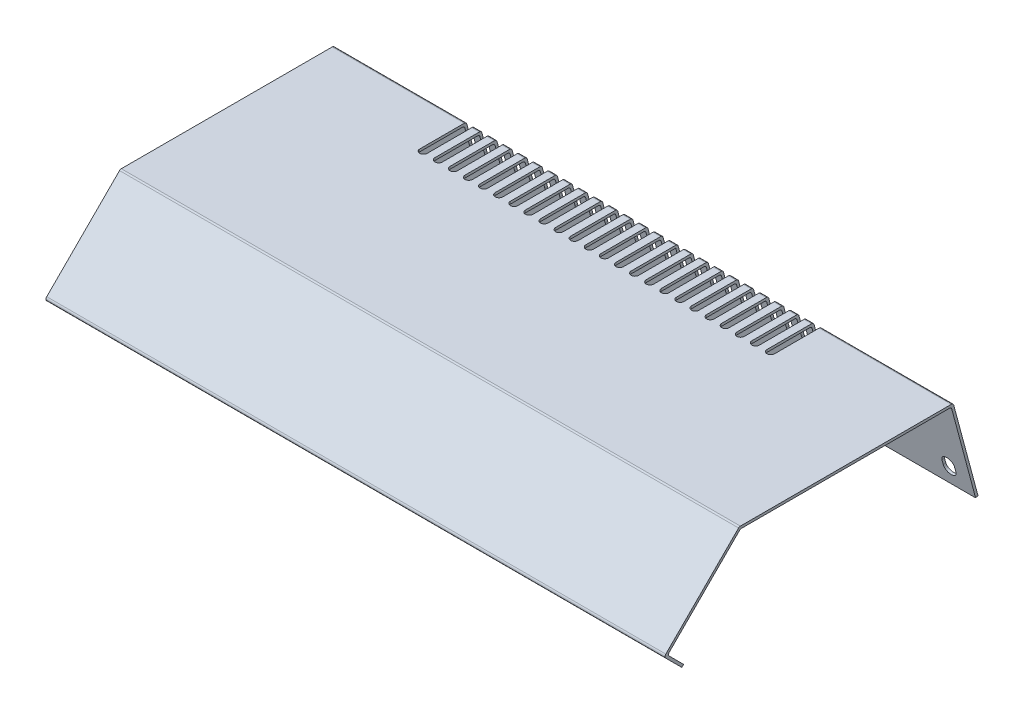
SolidWorks part; units mm, degrees
material "1023 Листовая углеродистая сталь (SS)"
ref_plane "Спереди" through (0, 0, 0) normal (0, 0, 1) x (1, 0, 0)
ref_plane "Сверху" through (0, 0, 0) normal (0, 1, 0) x (1, 0, 0)
ref_plane "Справа" through (0, 0, 0) normal (1, 0, 0) x (0, 0, -1)
sketch "Эскиз1" plane through (0, 0, 0) normal (1, 0, 0) x (0, 0, -1)
  line L2 (-42.5, 37) -> (42.5, 37)
  line L3 (-72.4289, 7.0711) -> (-42.5, 37)
  line L4 (42.5, 37) -> (52.3448, 0.2588)
  line L14 (-72.4289, 7.0711) -> (-65.3579, 0)
  line L15 (-71.0147, 7.0711) -> (-64.6508, 0.7071)
  line L16 (-71.0147, 7.0711) -> (-42.0858, 36)
  line L17 (-42.0858, 36) -> (41.7327, 36)
  line L18 (41.7327, 36) -> (51.3788, 0)
  line L19 (-65.3579, 0) -> (-64.6508, 0.7071)
  line L20 (51.3788, 0) -> (52.3448, 0.2588)
  point P8 (0, 37)
  dimension "D1" = 105
  dimension "D2" = 37
  dimension "D3" = 85
  dimension "D4" = 135
  dimension "D5" = 10
  dimension "D6" = 1
extrude "Бобышка-Вытянуть1" add sketch "Эскиз1" along normal mid plane 246
sketch "Эскиз2" plane through (0, 37, 0) normal (0, 1, 0) x (1, 0, 0)
  line L0 (0, 0) -> (0, 58.0016) construction
  line L1 (-70.5, 42.5) -> (-70.5, 24)
  line L2 (-70.5, 42.5) -> (-67.5, 42.5)
  line L3 (-67.5, 42.5) -> (-67.5, 24)
  line L4 (123, 42.5) -> (-123, 42.5) construction
  line L5 (-64.5, 42.5) -> (-64.5, 24)
  line L6 (-61.5, 42.5) -> (-61.5, 24)
  line L7 (-64.5, 42.5) -> (-61.5, 42.5)
  line L8 (-58.5, 42.5) -> (-58.5, 24)
  line L9 (-55.5, 42.5) -> (-55.5, 24)
  line L10 (-58.5, 42.5) -> (-55.5, 42.5)
  line L11 (-52.5, 42.5) -> (-52.5, 24)
  line L12 (-49.5, 42.5) -> (-49.5, 24)
  line L13 (-52.5, 42.5) -> (-49.5, 42.5)
  line L14 (-46.5, 42.5) -> (-46.5, 24)
  line L15 (-43.5, 42.5) -> (-43.5, 24)
  line L16 (-46.5, 42.5) -> (-43.5, 42.5)
  line L17 (-40.5, 42.5) -> (-40.5, 24)
  line L18 (-37.5, 42.5) -> (-37.5, 24)
  line L19 (-40.5, 42.5) -> (-37.5, 42.5)
  line L20 (-34.5, 42.5) -> (-34.5, 24)
  line L21 (-31.5, 42.5) -> (-31.5, 24)
  line L22 (-34.5, 42.5) -> (-31.5, 42.5)
  line L23 (-28.5, 42.5) -> (-28.5, 24)
  line L24 (-25.5, 42.5) -> (-25.5, 24)
  line L25 (-28.5, 42.5) -> (-25.5, 42.5)
  line L26 (-22.5, 42.5) -> (-22.5, 24)
  line L27 (-19.5, 42.5) -> (-19.5, 24)
  line L28 (-22.5, 42.5) -> (-19.5, 42.5)
  line L29 (-16.5, 42.5) -> (-16.5, 24)
  line L30 (-13.5, 42.5) -> (-13.5, 24)
  line L31 (-16.5, 42.5) -> (-13.5, 42.5)
  line L32 (-10.5, 42.5) -> (-10.5, 24)
  line L33 (-7.5, 42.5) -> (-7.5, 24)
  line L34 (-10.5, 42.5) -> (-7.5, 42.5)
  line L35 (-4.5, 42.5) -> (-4.5, 24)
  line L36 (-1.5, 42.5) -> (-1.5, 24)
  line L37 (-4.5, 42.5) -> (-1.5, 42.5)
  line L38 (1.5, 42.5) -> (1.5, 24)
  line L39 (4.5, 42.5) -> (4.5, 24)
  line L40 (1.5, 42.5) -> (4.5, 42.5)
  line L41 (7.5, 42.5) -> (7.5, 24)
  line L42 (10.5, 42.5) -> (10.5, 24)
  line L43 (7.5, 42.5) -> (10.5, 42.5)
  line L44 (13.5, 42.5) -> (13.5, 24)
  line L45 (16.5, 42.5) -> (16.5, 24)
  line L46 (13.5, 42.5) -> (16.5, 42.5)
  line L47 (19.5, 42.5) -> (19.5, 24)
  line L48 (22.5, 42.5) -> (22.5, 24)
  line L49 (19.5, 42.5) -> (22.5, 42.5)
  line L50 (25.5, 42.5) -> (25.5, 24)
  line L51 (28.5, 42.5) -> (28.5, 24)
  line L52 (25.5, 42.5) -> (28.5, 42.5)
  line L53 (31.5, 42.5) -> (31.5, 24)
  line L54 (34.5, 42.5) -> (34.5, 24)
  line L55 (31.5, 42.5) -> (34.5, 42.5)
  line L56 (37.5, 42.5) -> (37.5, 24)
  line L57 (40.5, 42.5) -> (40.5, 24)
  line L58 (37.5, 42.5) -> (40.5, 42.5)
  line L59 (43.5, 42.5) -> (43.5, 24)
  line L60 (46.5, 42.5) -> (46.5, 24)
  line L61 (43.5, 42.5) -> (46.5, 42.5)
  line L62 (49.5, 42.5) -> (49.5, 24)
  line L63 (52.5, 42.5) -> (52.5, 24)
  line L64 (49.5, 42.5) -> (52.5, 42.5)
  line L65 (55.5, 42.5) -> (55.5, 24)
  line L66 (58.5, 42.5) -> (58.5, 24)
  line L67 (55.5, 42.5) -> (58.5, 42.5)
  line L68 (61.5, 42.5) -> (61.5, 24)
  line L69 (64.5, 42.5) -> (64.5, 24)
  line L70 (61.5, 42.5) -> (64.5, 42.5)
  line L71 (67.5, 42.5) -> (67.5, 24)
  line L72 (70.5, 42.5) -> (70.5, 24)
  line L73 (67.5, 42.5) -> (70.5, 42.5)
  arc A0 (-67.5, 24) -> (-70.5, 24) centre (-69, 24) cw
  arc A1 (-61.5, 24) -> (-64.5, 24) centre (-63, 24) cw
  arc A2 (-55.5, 24) -> (-58.5, 24) centre (-57, 24) cw
  arc A3 (-49.5, 24) -> (-52.5, 24) centre (-51, 24) cw
  arc A4 (-43.5, 24) -> (-46.5, 24) centre (-45, 24) cw
  arc A5 (-37.5, 24) -> (-40.5, 24) centre (-39, 24) cw
  arc A6 (-31.5, 24) -> (-34.5, 24) centre (-33, 24) cw
  arc A7 (-25.5, 24) -> (-28.5, 24) centre (-27, 24) cw
  arc A8 (-19.5, 24) -> (-22.5, 24) centre (-21, 24) cw
  arc A9 (-13.5, 24) -> (-16.5, 24) centre (-15, 24) cw
  arc A10 (-7.5, 24) -> (-10.5, 24) centre (-9, 24) cw
  arc A11 (-1.5, 24) -> (-4.5, 24) centre (-3, 24) cw
  arc A12 (4.5, 24) -> (1.5, 24) centre (3, 24) cw
  arc A13 (10.5, 24) -> (7.5, 24) centre (9, 24) cw
  arc A14 (16.5, 24) -> (13.5, 24) centre (15, 24) cw
  arc A15 (22.5, 24) -> (19.5, 24) centre (21, 24) cw
  arc A16 (28.5, 24) -> (25.5, 24) centre (27, 24) cw
  arc A17 (34.5, 24) -> (31.5, 24) centre (33, 24) cw
  arc A18 (40.5, 24) -> (37.5, 24) centre (39, 24) cw
  arc A19 (46.5, 24) -> (43.5, 24) centre (45, 24) cw
  arc A20 (52.5, 24) -> (49.5, 24) centre (51, 24) cw
  arc A21 (58.5, 24) -> (55.5, 24) centre (57, 24) cw
  arc A22 (64.5, 24) -> (61.5, 24) centre (63, 24) cw
  arc A23 (70.5, 24) -> (67.5, 24) centre (69, 24) cw
  point P10 (-69, 22.5)
  dimension "D1" = 3
  dimension "D2" = 20
  dimension "D3" = 24
extrude "Вырез-Вытянуть1" cut sketch "Эскиз2" against normal blind 10
sketch "Эскиз3" plane through (0, 13.1035, -48.903) normal (0, 0.2588, -0.9659) x (-1, 0, 0)
  line L0 (0, 0) -> (0, 49.0276) construction
  line L1 (-70.5, 24.7394) -> (-70.5, 16.2394)
  line L2 (-67.5, 24.7394) -> (-67.5, 16.2394)
  line L3 (-70.5, 24.7394) -> (-67.5, 24.7394)
  line L4 (-64.5, 24.7394) -> (-61.5, 24.7394)
  line L5 (-64.5, 24.7394) -> (-64.5, 16.2394)
  line L6 (-61.5, 24.7394) -> (-61.5, 16.2394)
  line L7 (-58.5, 24.7394) -> (-55.5, 24.7394)
  line L8 (-58.5, 24.7394) -> (-58.5, 16.2394)
  line L9 (-55.5, 24.7394) -> (-55.5, 16.2394)
  line L10 (-52.5, 24.7394) -> (-49.5, 24.7394)
  line L11 (-52.5, 24.7394) -> (-52.5, 16.2394)
  line L12 (-49.5, 24.7394) -> (-49.5, 16.2394)
  line L13 (-46.5, 24.7394) -> (-43.5, 24.7394)
  line L14 (-46.5, 24.7394) -> (-46.5, 16.2394)
  line L15 (-43.5, 24.7394) -> (-43.5, 16.2394)
  line L16 (-40.5, 24.7394) -> (-37.5, 24.7394)
  line L17 (-40.5, 24.7394) -> (-40.5, 16.2394)
  line L18 (-37.5, 24.7394) -> (-37.5, 16.2394)
  line L19 (-34.5, 24.7394) -> (-31.5, 24.7394)
  line L20 (-34.5, 24.7394) -> (-34.5, 16.2394)
  line L21 (-31.5, 24.7394) -> (-31.5, 16.2394)
  line L22 (-28.5, 24.7394) -> (-25.5, 24.7394)
  line L23 (-28.5, 24.7394) -> (-28.5, 16.2394)
  line L24 (-25.5, 24.7394) -> (-25.5, 16.2394)
  line L25 (-22.5, 24.7394) -> (-19.5, 24.7394)
  line L26 (-22.5, 24.7394) -> (-22.5, 16.2394)
  line L27 (-19.5, 24.7394) -> (-19.5, 16.2394)
  line L28 (-16.5, 24.7394) -> (-13.5, 24.7394)
  line L29 (-16.5, 24.7394) -> (-16.5, 16.2394)
  line L30 (-13.5, 24.7394) -> (-13.5, 16.2394)
  line L31 (-10.5, 24.7394) -> (-7.5, 24.7394)
  line L32 (-10.5, 24.7394) -> (-10.5, 16.2394)
  line L33 (-7.5, 24.7394) -> (-7.5, 16.2394)
  line L34 (-4.5, 24.7394) -> (-1.5, 24.7394)
  line L35 (-4.5, 24.7394) -> (-4.5, 16.2394)
  line L36 (-1.5, 24.7394) -> (-1.5, 16.2394)
  line L37 (1.5, 24.7394) -> (4.5, 24.7394)
  line L38 (1.5, 24.7394) -> (1.5, 16.2394)
  line L39 (4.5, 24.7394) -> (4.5, 16.2394)
  line L40 (7.5, 24.7394) -> (10.5, 24.7394)
  line L41 (7.5, 24.7394) -> (7.5, 16.2394)
  line L42 (10.5, 24.7394) -> (10.5, 16.2394)
  line L43 (13.5, 24.7394) -> (16.5, 24.7394)
  line L44 (13.5, 24.7394) -> (13.5, 16.2394)
  line L45 (16.5, 24.7394) -> (16.5, 16.2394)
  line L46 (19.5, 24.7394) -> (22.5, 24.7394)
  line L47 (19.5, 24.7394) -> (19.5, 16.2394)
  line L48 (22.5, 24.7394) -> (22.5, 16.2394)
  line L49 (25.5, 24.7394) -> (28.5, 24.7394)
  line L50 (25.5, 24.7394) -> (25.5, 16.2394)
  line L51 (28.5, 24.7394) -> (28.5, 16.2394)
  line L52 (31.5, 24.7394) -> (34.5, 24.7394)
  line L53 (31.5, 24.7394) -> (31.5, 16.2394)
  line L54 (34.5, 24.7394) -> (34.5, 16.2394)
  line L55 (37.5, 24.7394) -> (40.5, 24.7394)
  line L56 (37.5, 24.7394) -> (37.5, 16.2394)
  line L57 (40.5, 24.7394) -> (40.5, 16.2394)
  line L58 (43.5, 24.7394) -> (46.5, 24.7394)
  line L59 (43.5, 24.7394) -> (43.5, 16.2394)
  line L60 (46.5, 24.7394) -> (46.5, 16.2394)
  line L61 (49.5, 24.7394) -> (52.5, 24.7394)
  line L62 (49.5, 24.7394) -> (49.5, 16.2394)
  line L63 (52.5, 24.7394) -> (52.5, 16.2394)
  line L64 (55.5, 24.7394) -> (58.5, 24.7394)
  line L65 (55.5, 24.7394) -> (55.5, 16.2394)
  line L66 (58.5, 24.7394) -> (58.5, 16.2394)
  line L67 (61.5, 24.7394) -> (64.5, 24.7394)
  line L68 (61.5, 24.7394) -> (61.5, 16.2394)
  line L69 (64.5, 24.7394) -> (64.5, 16.2394)
  line L70 (67.5, 24.7394) -> (70.5, 24.7394)
  line L71 (67.5, 24.7394) -> (67.5, 16.2394)
  line L72 (70.5, 24.7394) -> (70.5, 16.2394)
  line L73 (-70.5, 24.7394) -> (-64.5, 24.7394) construction
  arc A0 (-67.5, 16.2394) -> (-70.5, 16.2394) centre (-69, 16.2394) cw
  arc A1 (-61.5, 16.2394) -> (-64.5, 16.2394) centre (-63, 16.2394) cw
  arc A2 (-55.5, 16.2394) -> (-58.5, 16.2394) centre (-57, 16.2394) cw
  arc A3 (-49.5, 16.2394) -> (-52.5, 16.2394) centre (-51, 16.2394) cw
  arc A4 (-43.5, 16.2394) -> (-46.5, 16.2394) centre (-45, 16.2394) cw
  arc A5 (-37.5, 16.2394) -> (-40.5, 16.2394) centre (-39, 16.2394) cw
  arc A6 (-31.5, 16.2394) -> (-34.5, 16.2394) centre (-33, 16.2394) cw
  arc A7 (-25.5, 16.2394) -> (-28.5, 16.2394) centre (-27, 16.2394) cw
  arc A8 (-19.5, 16.2394) -> (-22.5, 16.2394) centre (-21, 16.2394) cw
  arc A9 (-13.5, 16.2394) -> (-16.5, 16.2394) centre (-15, 16.2394) cw
  arc A10 (-7.5, 16.2394) -> (-10.5, 16.2394) centre (-9, 16.2394) cw
  arc A11 (-1.5, 16.2394) -> (-4.5, 16.2394) centre (-3, 16.2394) cw
  arc A12 (4.5, 16.2394) -> (1.5, 16.2394) centre (3, 16.2394) cw
  arc A13 (10.5, 16.2394) -> (7.5, 16.2394) centre (9, 16.2394) cw
  arc A14 (16.5, 16.2394) -> (13.5, 16.2394) centre (15, 16.2394) cw
  arc A15 (22.5, 16.2394) -> (19.5, 16.2394) centre (21, 16.2394) cw
  arc A16 (28.5, 16.2394) -> (25.5, 16.2394) centre (27, 16.2394) cw
  arc A17 (34.5, 16.2394) -> (31.5, 16.2394) centre (33, 16.2394) cw
  arc A18 (40.5, 16.2394) -> (37.5, 16.2394) centre (39, 16.2394) cw
  arc A19 (46.5, 16.2394) -> (43.5, 16.2394) centre (45, 16.2394) cw
  arc A20 (52.5, 16.2394) -> (49.5, 16.2394) centre (51, 16.2394) cw
  arc A21 (58.5, 16.2394) -> (55.5, 16.2394) centre (57, 16.2394) cw
  arc A22 (64.5, 16.2394) -> (61.5, 16.2394) centre (63, 16.2394) cw
  arc A23 (70.5, 16.2394) -> (67.5, 16.2394) centre (69, 16.2394) cw
  point P10 (-69, 14.7394)
  dimension "D1" = 10
  dimension "D3" = 6
  dimension "D2" = 24
extrude "Вырез-Вытянуть2" cut sketch "Эскиз3" against normal blind 10
sketch "Эскиз4" plane through (0, 13.1035, -48.903) normal (0, 0.2588, -0.9659) x (-1, 0, 0)
  line L0 (0, 0) -> (0, 41.1257) construction
  line L1 (-117, -6.2978) -> (-117, -4.2978)
  line L2 (-112, -6.2978) -> (-112, -4.2978)
  line L3 (-123, -13.2978) -> (123, -13.2978) construction
  line L4 (-123, -13.2978) -> (-123, 24.7394) construction
  line L5 (112, -6.2978) -> (112, -4.2978)
  line L6 (117, -6.2978) -> (117, -4.2978)
  arc A0 (-112, -4.2978) -> (-117, -4.2978) centre (-114.5, -4.2978) ccw
  arc A1 (-117, -6.2978) -> (-112, -6.2978) centre (-114.5, -6.2978) ccw
  arc A2 (112, -4.2978) -> (117, -4.2978) centre (114.5, -4.2978) cw
  arc A3 (117, -6.2978) -> (112, -6.2978) centre (114.5, -6.2978) cw
  point P9 (-117, -5.2978)
  point P10 (-114.5, -1.7978)
  point P11 (-114.5, -8.7978)
  dimension "D2" = 7
  dimension "D1" = 5
  dimension "D3" = 4.5
  dimension "D4" = 6
extrude "Вырез-Вытянуть3" cut sketch "Эскиз4" against normal up to next
fillet "Скругление1" radius 1 53 edges at (-66, 36, -41.7327) (-60, 36, -41.7327) (-54, 36, -41.7327) (-48, 36, -41.7327) (-42, 36, -41.7327) (-36, 36, -41.7327) (-30, 36, -41.7327) (-24, 36, -41.7327) (-18, 36, -41.7327) (-12, 36, -41.7327) (-6, 36, -41.7327) (0, 36, -41.7327) (6, 36, -41.7327) (18, 36, -41.7327) (24, 36, -41.7327) (30, 36, -41.7327) (36, 36, -41.7327) (42, 36, -41.7327) (48, 36, -41.7327) (54, 36, -41.7327) (60, 36, -41.7327) (66, 36, -41.7327) (-66, 37, -42.5) (-60, 37, -42.5) (-54, 37, -42.5) (-48, 37, -42.5) (-42, 37, -42.5) (-36, 37, -42.5) (-30, 37, -42.5) (-24, 37, -42.5) (-18, 37, -42.5) (-12, 37, -42.5) (-6, 37, -42.5) (0, 37, -42.5) (6, 37, -42.5) (12, 37, -42.5) (18, 37, -42.5) (24, 37, -42.5) (30, 37, -42.5) (36, 37, -42.5) (42, 37, -42.5) (48, 37, -42.5) (54, 37, -42.5) (60, 37, -42.5) (66, 37, -42.5) (-96.75, 37, -42.5) (96.75, 37, -42.5) (-96.75, 36, -41.7327) (96.75, 36, -41.7327) (0, 36, 42.0858) (0, 7.0711, 71.0147) (0, 7.0711, 72.4289) (0, 37, 42.5)
